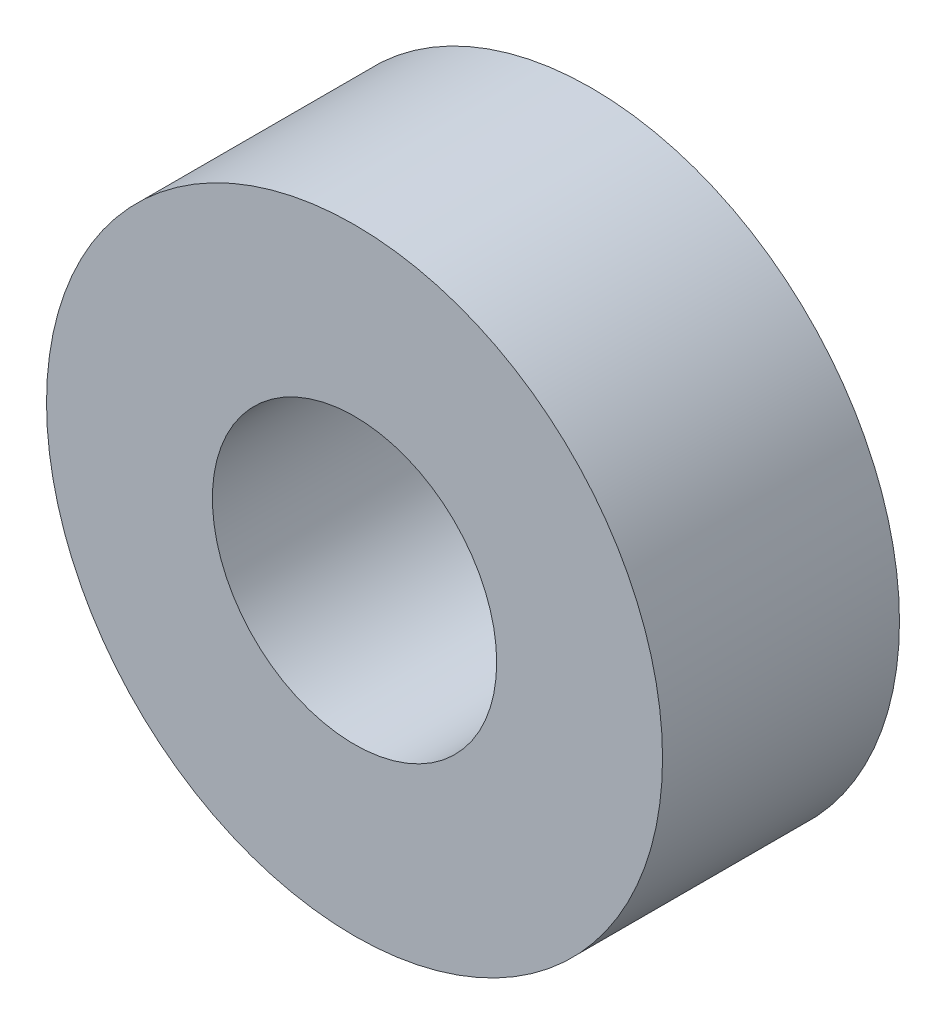
SolidWorks part; units mm, degrees
material "Brass"
ref_plane "Front Plane" through (0, 0, 0) normal (0, 0, 1) x (1, 0, 0)
ref_plane "Top Plane" through (0, 0, 0) normal (0, 1, 0) x (1, 0, 0)
ref_plane "Right Plane" through (0, 0, 0) normal (1, 0, 0) x (0, 0, -1)
sketch "Sketch1" plane through (0, 0, 0) normal (0, 0, 1) x (1, 0, 0)
  circle A0 centre (0, 0) radius 6.5
  circle A1 centre (0, 0) radius 3
  dimension "D1" = 13
  dimension "D2" = 6
extrude "Boss-Extrude1" add sketch "Sketch1" along normal blind 5
